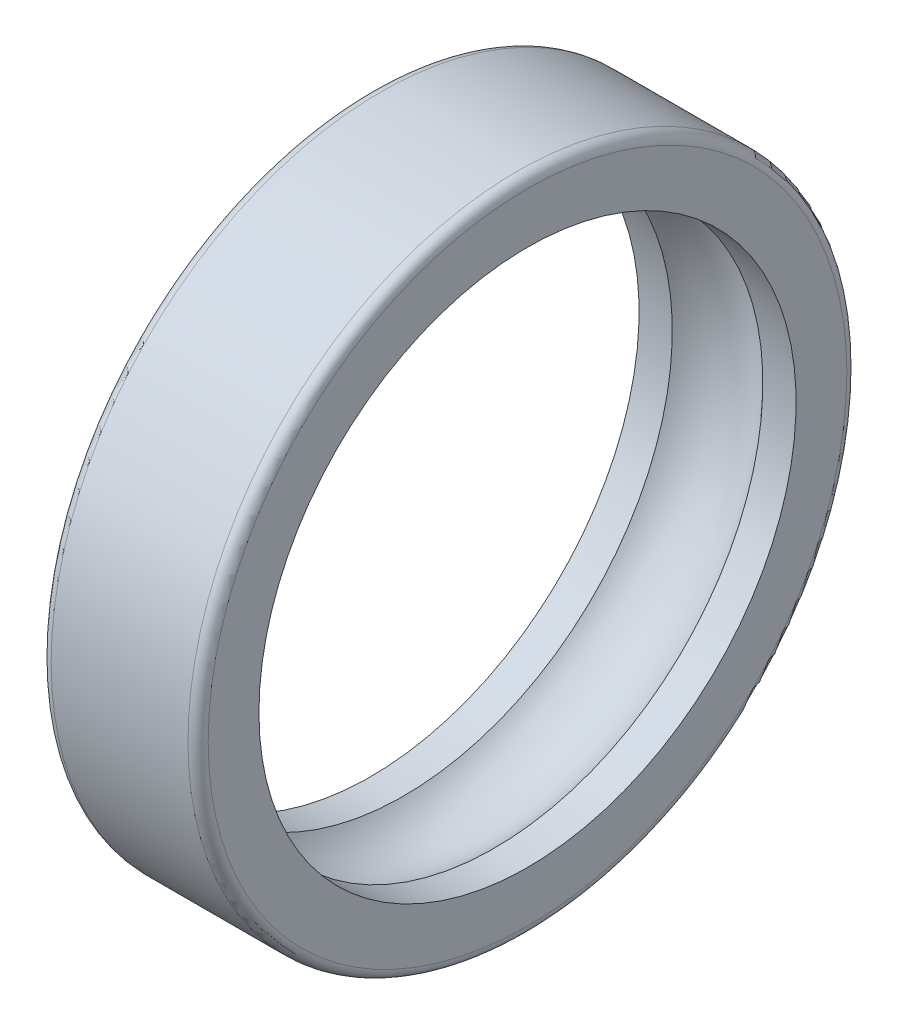
SolidWorks part; units mm, degrees
ref_plane "Front" through (0, 0, 0) normal (0, 0, 1) x (1, 0, 0)
ref_plane "Top" through (0, 0, 0) normal (0, 1, 0) x (1, 0, 0)
ref_plane "Right" through (0, 0, 0) normal (1, 0, 0) x (0, 0, -1)
sketch "草图1" plane through (0, 0, 0) normal (0, 0, 1) x (1, 0, 0)
  line L0 (0, 0) -> (0, 13.615) construction
  line L1 (2.0616, 12.23) -> (3.575, 12.23)
  line L2 (-3.575, 15) -> (3.575, 15)
  line L3 (-3.575, 15) -> (-3.575, 12.23)
  line L4 (-3.575, 12.23) -> (-2.0616, 12.23)
  line L5 (3.575, 15) -> (3.575, 12.23)
  line L6 (-3.575, 15) -> (3.575, 12.23) construction
  line L7 (-3.575, 12.23) -> (3.575, 15) construction
  line L8 (0, 0) -> (5.1054, 0) construction
  arc A0 (-2.0616, 12.23) -> (2.0616, 12.23) centre (0, 10.38) cw
  dimension "D2" = 2.77
  dimension "D1" = 1.85
  dimension "D3" = 2.77
  dimension "D4" = 7.15
  dimension "D5" = 15
revolve "旋转1" add sketch "草图1" angle 360 about L8
fillet "圆角1" radius 0.46 2 edges at (3.575, 0, 15) (-3.575, 0, 15)
